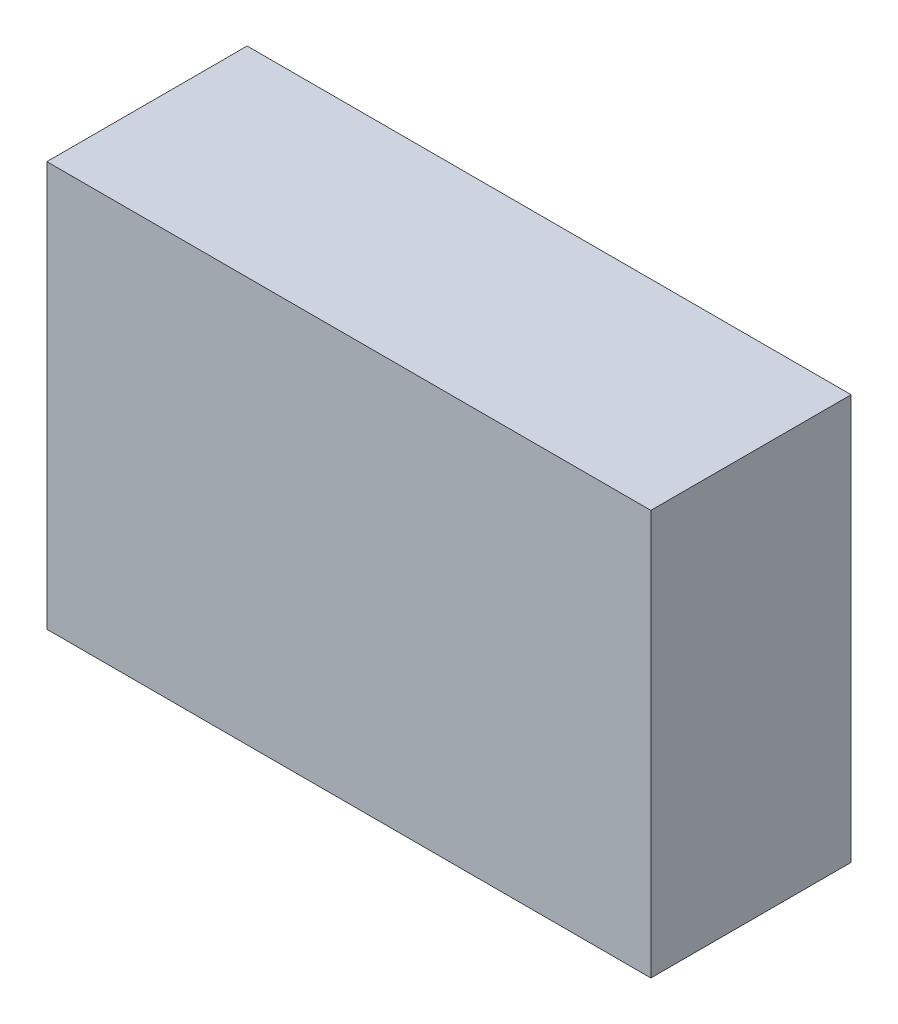
SolidWorks part; units mm, degrees
ref_plane "Plan de face" through (0, 0, 0) normal (0, 0, 1) x (1, 0, 0)
ref_plane "Plan de dessus" through (0, 0, 0) normal (0, 1, 0) x (1, 0, 0)
ref_plane "Plan de droite" through (0, 0, 0) normal (1, 0, 0) x (0, 0, -1)
sketch "Esquisse1" plane through (0, 0, 0) normal (0, 0, 1) x (1, 0, 0)
  line L1 (47.5, -31.85) -> (-47.5, -31.85)
  line L2 (47.5, -31.85) -> (47.5, 31.85)
  line L3 (47.5, 31.85) -> (-47.5, 31.85)
  line L4 (-47.5, -31.85) -> (-47.5, 31.85)
  line L5 (47.5, -31.85) -> (-47.5, 31.85) construction
  line L6 (47.5, 31.85) -> (-47.5, -31.85) construction
  point P0 (0, 0)
  dimension "D1" = 63.7
  dimension "D2" = 95
extrude "Boss.-Extru.1" add sketch "Esquisse1" along normal blind 31.5
